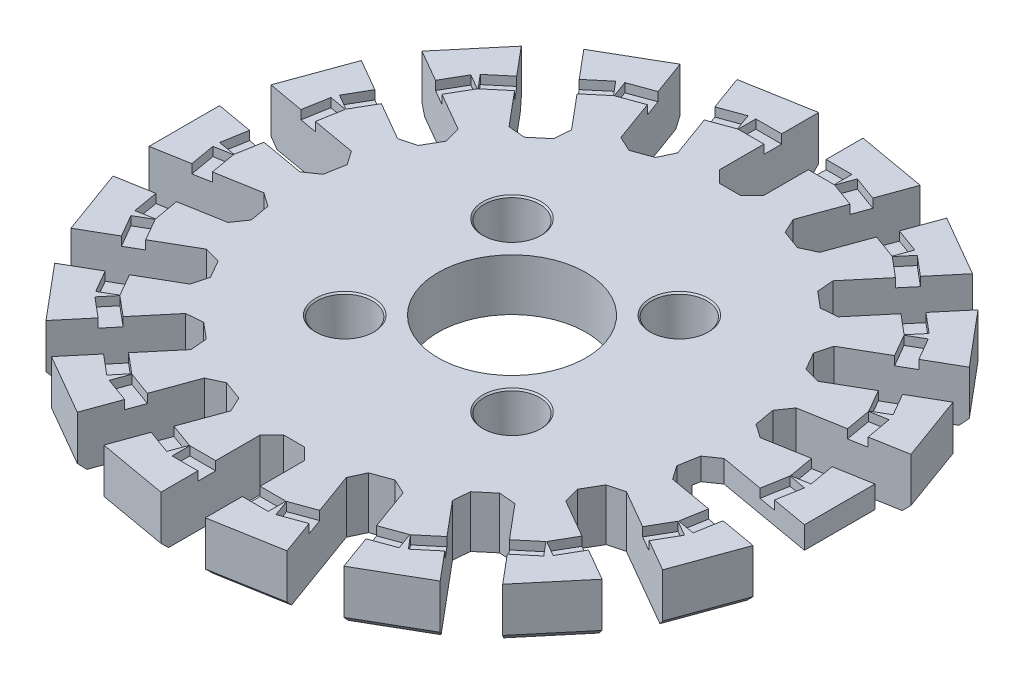
SolidWorks part; units mm, degrees
ref_plane "Front Plane" through (0, 0, 0) normal (0, 0, 1) x (1, 0, 0)
ref_plane "Top Plane" through (0, 0, 0) normal (0, 1, 0) x (1, 0, 0)
ref_plane "Right Plane" through (0, 0, 0) normal (1, 0, 0) x (0, 0, -1)
sketch "Sketch1" plane through (0, 0, 0) normal (0, 1, 0) x (1, 0, 0)
  line L0 (-1.5, 22.2355) -> (-1.5, 14.7355)
  line L1 (-1.5, 22.2355) -> (-6.1955, 21.4076)
  line L2 (-9.0145, 20.3815) -> (-13.1436, 17.9976)
  line L3 (-15.4418, 16.0692) -> (-18.5065, 12.4168)
  line L4 (-20.0065, 9.8187) -> (-21.6372, 5.3384)
  line L5 (-22.1582, 2.3839) -> (-22.1582, -2.3839)
  line L6 (-21.6372, -5.3384) -> (-20.0065, -9.8187)
  line L7 (-18.5065, -12.4168) -> (-15.4418, -16.0692)
  line L8 (-13.1436, -17.9976) -> (-9.0145, -20.3815)
  line L9 (-6.1955, -21.4076) -> (-1.5, -22.2355)
  line L10 (1.5, -22.2355) -> (6.1955, -21.4076)
  line L11 (9.0145, -20.3815) -> (13.1436, -17.9976)
  line L12 (15.4418, -16.0692) -> (18.5065, -12.4168)
  line L13 (20.0065, -9.8187) -> (21.6372, -5.3384)
  line L14 (22.1582, -2.3839) -> (22.1582, 2.3839)
  line L15 (21.6372, 5.3384) -> (20.0065, 9.8187)
  line L16 (18.5065, 12.4168) -> (15.4418, 16.0692)
  line L17 (13.1436, 17.9976) -> (9.0145, 20.3815)
  line L18 (6.1955, 21.4076) -> (1.5, 22.2355)
  line L19 (-1.5, 14.7355) -> (1.5, 14.7355)
  line L20 (1.5, 14.7355) -> (1.5, 22.2355)
  line L21 (6.4494, 13.3338) -> (9.0145, 20.3815)
  line L22 (3.6303, 14.3599) -> (6.4494, 13.3338)
  line L23 (6.1955, 21.4076) -> (3.6303, 14.3599)
  line L24 (10.6209, 10.3239) -> (15.4418, 16.0692)
  line L25 (8.3227, 12.2522) -> (10.6209, 10.3239)
  line L26 (13.1436, 17.9976) -> (8.3227, 12.2522)
  line L27 (13.5113, 6.0687) -> (20.0065, 9.8187)
  line L28 (12.0113, 8.6668) -> (13.5113, 6.0687)
  line L29 (18.5065, 12.4168) -> (12.0113, 8.6668)
  line L30 (14.7721, 1.0816) -> (22.1582, 2.3839)
  line L31 (14.2512, 4.036) -> (14.7721, 1.0816)
  line L32 (21.6372, 5.3384) -> (14.2512, 4.036)
  line L33 (14.2512, -4.036) -> (21.6372, -5.3384)
  line L34 (14.7721, -1.0816) -> (14.2512, -4.036)
  line L35 (22.1582, -2.3839) -> (14.7721, -1.0816)
  line L36 (12.0113, -8.6668) -> (18.5065, -12.4168)
  line L37 (13.5113, -6.0687) -> (12.0113, -8.6668)
  line L38 (20.0065, -9.8187) -> (13.5113, -6.0687)
  line L39 (8.3227, -12.2522) -> (13.1436, -17.9976)
  line L40 (10.6209, -10.3239) -> (8.3227, -12.2522)
  line L41 (15.4418, -16.0692) -> (10.6209, -10.3239)
  line L42 (3.6303, -14.3599) -> (6.1955, -21.4076)
  line L43 (6.4494, -13.3338) -> (3.6303, -14.3599)
  line L44 (9.0145, -20.3815) -> (6.4494, -13.3338)
  line L45 (-1.5, -14.7355) -> (-1.5, -22.2355)
  line L46 (1.5, -14.7355) -> (-1.5, -14.7355)
  line L47 (1.5, -22.2355) -> (1.5, -14.7355)
  line L48 (-6.4494, -13.3338) -> (-9.0145, -20.3815)
  line L49 (-3.6303, -14.3599) -> (-6.4494, -13.3338)
  line L50 (-6.1955, -21.4076) -> (-3.6303, -14.3599)
  line L51 (-10.6209, -10.3239) -> (-15.4418, -16.0692)
  line L52 (-8.3227, -12.2522) -> (-10.6209, -10.3239)
  line L53 (-13.1436, -17.9976) -> (-8.3227, -12.2522)
  line L54 (-13.5113, -6.0687) -> (-20.0065, -9.8187)
  line L55 (-12.0113, -8.6668) -> (-13.5113, -6.0687)
  line L56 (-18.5065, -12.4168) -> (-12.0113, -8.6668)
  line L57 (-14.7721, -1.0816) -> (-22.1582, -2.3839)
  line L58 (-14.2512, -4.036) -> (-14.7721, -1.0816)
  line L59 (-21.6372, -5.3384) -> (-14.2512, -4.036)
  line L60 (-14.2512, 4.036) -> (-21.6372, 5.3384)
  line L61 (-14.7721, 1.0816) -> (-14.2512, 4.036)
  line L62 (-22.1582, 2.3839) -> (-14.7721, 1.0816)
  line L63 (-12.0113, 8.6668) -> (-18.5065, 12.4168)
  line L64 (-13.5113, 6.0687) -> (-12.0113, 8.6668)
  line L65 (-20.0065, 9.8187) -> (-13.5113, 6.0687)
  line L66 (-8.3227, 12.2522) -> (-13.1436, 17.9976)
  line L67 (-10.6209, 10.3239) -> (-8.3227, 12.2522)
  line L68 (-15.4418, 16.0692) -> (-10.6209, 10.3239)
  line L69 (-3.6303, 14.3599) -> (-6.1955, 21.4076)
  line L70 (-6.4494, 13.3338) -> (-3.6303, 14.3599)
  line L71 (-9.0145, 20.3815) -> (-6.4494, 13.3338)
  arc A0 (6.1516, 21.2871) -> (1.5, 22.1073) centre (0, 0) ccw construction
  arc A1 (13.0613, 17.8994) -> (8.9707, 20.2611) centre (0, 0) ccw construction
  arc A2 (18.3955, 12.3527) -> (15.3594, 15.971) centre (0, 0) ccw construction
  arc A3 (21.511, 5.3161) -> (19.8955, 9.7546) centre (0, 0) ccw construction
  arc A4 (22.032, -2.3617) -> (22.032, 2.3617) centre (0, 0) ccw construction
  arc A5 (19.8955, -9.7546) -> (21.511, -5.3161) centre (0, 0) ccw construction
  arc A6 (-8.9707, 20.2611) -> (-13.0613, 17.8994) centre (0, 0) ccw construction
  arc A7 (-15.3594, 15.971) -> (-18.3955, 12.3527) centre (0, 0) ccw construction
  arc A8 (-19.8955, 9.7546) -> (-21.511, 5.3161) centre (0, 0) ccw construction
  arc A9 (-22.032, 2.3617) -> (-22.032, -2.3617) centre (0, 0) ccw construction
  arc A10 (-21.511, -5.3161) -> (-19.8955, -9.7546) centre (0, 0) ccw construction
  arc A11 (-18.3955, -12.3527) -> (-15.3594, -15.971) centre (0, 0) ccw construction
  arc A12 (-13.0613, -17.8994) -> (-8.9707, -20.2611) centre (0, 0) ccw construction
  arc A13 (-6.1516, -21.2871) -> (-1.5, -22.1073) centre (0, 0) ccw construction
  arc A14 (1.5, -22.1073) -> (6.1516, -21.2871) centre (0, 0) ccw construction
  arc A15 (8.9707, -20.2611) -> (13.0613, -17.8994) centre (0, 0) ccw construction
  arc A16 (15.3594, -15.971) -> (18.3955, -12.3527) centre (0, 0) ccw construction
  arc A17 (-1.5, 22.1073) -> (-6.1516, 21.2871) centre (0, 0) ccw construction
  point P96 (0, 0)
  dimension "D1" = 44.3163
  dimension "D2" = 3
  dimension "D3" = 1.5
  dimension "D4" = 7.5
  dimension "D5" = 18
extrude "Boss-Extrude1" add sketch "Sketch1" along normal blind 3.5
chamfer "Chamfer1" distance 0.8 angle 45 36 edges at (-10.6209, 1.75, 10.3239) (-8.3227, 1.75, 12.2522) (-3.6303, 1.75, 14.3599) (1.5, 1.75, 14.7355) (6.4494, 1.75, 13.3338) (10.6209, 1.75, 10.3239) (13.5113, 1.75, 6.0687) (-6.4494, 1.75, 13.3338) (-1.5, 1.75, 14.7355) (3.6303, 1.75, 14.3599) (8.3227, 1.75, 12.2522) (12.0113, 1.75, 8.6668) (14.7721, 1.75, 1.0816) (14.2512, 1.75, -4.036) (12.0113, 1.75, -8.6668) (8.3227, 1.75, -12.2522) (14.2512, 1.75, 4.036) (14.7721, 1.75, -1.0816) (13.5113, 1.75, -6.0687) (10.6209, 1.75, -10.3239) (3.6303, 1.75, -14.3599) (-1.5, 1.75, -14.7355) (-13.5113, 1.75, -6.0687) (-10.6209, 1.75, -10.3239) (-6.4494, 1.75, -13.3338) (1.5, 1.75, -14.7355) (-3.6303, 1.75, -14.3599) (-8.3227, 1.75, -12.2522) (-12.0113, 1.75, -8.6668) (-14.7721, 1.75, -1.0816) (-14.2512, 1.75, -4.036) (-14.2512, 1.75, 4.036) (-14.7721, 1.75, 1.0816) (-12.0113, 1.75, 8.6668) (-13.5113, 1.75, 6.0687) (6.4494, 1.75, -13.3338)
sketch "Sketch2" plane through (0, 3.5, 0) normal (0, 1, 0) x (1, 0, 0)
  line L0 (-3.25, 19.7355) -> (3.25, 19.7355)
  line L2 (3.25, 19.7355) -> (3.25, 18.5355)
  line L3 (3.25, 18.5355) -> (-3.25, 18.5355)
  line L4 (-3.25, 18.5355) -> (-3.25, 19.7355)
  line L5 (3.2855, 18.5292) -> (3.6959, 19.6569)
  line L6 (3.6959, 19.6569) -> (9.8039, 17.4337)
  line L7 (9.8039, 17.4337) -> (9.3935, 16.3061)
  line L8 (9.3935, 16.3061) -> (3.2855, 18.5292)
  line L9 (9.4248, 16.2881) -> (10.1961, 17.2073)
  line L10 (10.1961, 17.2073) -> (15.1754, 13.0292)
  line L11 (15.1754, 13.0292) -> (14.404, 12.11)
  line L12 (14.404, 12.11) -> (9.4248, 16.2881)
  line L13 (14.4272, 12.0823) -> (15.4665, 12.6823)
  line L14 (15.4665, 12.6823) -> (18.7165, 7.0532)
  line L15 (18.7165, 7.0532) -> (17.6772, 6.4532)
  line L16 (17.6772, 6.4532) -> (14.4272, 12.0823)
  line L17 (17.6896, 6.4193) -> (18.8713, 6.6277)
  line L18 (18.8713, 6.6277) -> (20, 0.2264)
  line L19 (20, 0.2264) -> (18.8183, 0.018)
  line L20 (18.8183, 0.018) -> (17.6896, 6.4193)
  line L21 (18.8183, -0.018) -> (20, -0.2264)
  line L22 (20, -0.2264) -> (18.8713, -6.6277)
  line L23 (18.8713, -6.6277) -> (17.6896, -6.4193)
  line L24 (17.6896, -6.4193) -> (18.8183, -0.018)
  line L25 (17.6772, -6.4532) -> (18.7165, -7.0532)
  line L26 (18.7165, -7.0532) -> (15.4665, -12.6823)
  line L27 (15.4665, -12.6823) -> (14.4272, -12.0823)
  line L28 (14.4272, -12.0823) -> (17.6772, -6.4532)
  line L29 (14.404, -12.11) -> (15.1754, -13.0292)
  line L30 (15.1754, -13.0292) -> (10.1961, -17.2073)
  line L31 (10.1961, -17.2073) -> (9.4248, -16.2881)
  line L32 (9.4248, -16.2881) -> (14.404, -12.11)
  line L33 (9.3935, -16.3061) -> (9.8039, -17.4337)
  line L34 (9.8039, -17.4337) -> (3.6959, -19.6569)
  line L35 (3.6959, -19.6569) -> (3.2855, -18.5292)
  line L36 (3.2855, -18.5292) -> (9.3935, -16.3061)
  line L37 (3.25, -18.5355) -> (3.25, -19.7355)
  line L38 (3.25, -19.7355) -> (-3.25, -19.7355)
  line L39 (-3.25, -19.7355) -> (-3.25, -18.5355)
  line L40 (-3.25, -18.5355) -> (3.25, -18.5355)
  line L41 (-3.2855, -18.5292) -> (-3.6959, -19.6569)
  line L42 (-3.6959, -19.6569) -> (-9.8039, -17.4337)
  line L43 (-9.8039, -17.4337) -> (-9.3935, -16.3061)
  line L44 (-9.3935, -16.3061) -> (-3.2855, -18.5292)
  line L45 (-9.4248, -16.2881) -> (-10.1961, -17.2073)
  line L46 (-10.1961, -17.2073) -> (-15.1754, -13.0292)
  line L47 (-15.1754, -13.0292) -> (-14.404, -12.11)
  line L48 (-14.404, -12.11) -> (-9.4248, -16.2881)
  line L49 (-14.4272, -12.0823) -> (-15.4665, -12.6823)
  line L50 (-15.4665, -12.6823) -> (-18.7165, -7.0532)
  line L51 (-18.7165, -7.0532) -> (-17.6772, -6.4532)
  line L52 (-17.6772, -6.4532) -> (-14.4272, -12.0823)
  line L53 (-17.6896, -6.4193) -> (-18.8713, -6.6277)
  line L54 (-18.8713, -6.6277) -> (-20, -0.2264)
  line L55 (-20, -0.2264) -> (-18.8183, -0.018)
  line L56 (-18.8183, -0.018) -> (-17.6896, -6.4193)
  line L57 (-18.8183, 0.018) -> (-20, 0.2264)
  line L58 (-20, 0.2264) -> (-18.8713, 6.6277)
  line L59 (-18.8713, 6.6277) -> (-17.6896, 6.4193)
  line L60 (-17.6896, 6.4193) -> (-18.8183, 0.018)
  line L61 (-17.6772, 6.4532) -> (-18.7165, 7.0532)
  line L62 (-18.7165, 7.0532) -> (-15.4665, 12.6823)
  line L63 (-15.4665, 12.6823) -> (-14.4272, 12.0823)
  line L64 (-14.4272, 12.0823) -> (-17.6772, 6.4532)
  line L65 (-14.404, 12.11) -> (-15.1754, 13.0292)
  line L66 (-15.1754, 13.0292) -> (-10.1961, 17.2073)
  line L67 (-10.1961, 17.2073) -> (-9.4248, 16.2881)
  line L68 (-9.4248, 16.2881) -> (-14.404, 12.11)
  line L69 (-9.3935, 16.3061) -> (-9.8039, 17.4337)
  line L70 (-9.8039, 17.4337) -> (-3.6959, 19.6569)
  line L71 (-3.6959, 19.6569) -> (-3.2855, 18.5292)
  line L72 (-3.2855, 18.5292) -> (-9.3935, 16.3061)
  line L73 (-22.1582, 2.3839) -> (-22.1582, -2.3839) construction
  point P75 (0, 0)
  dimension "D1" = 6.5
  dimension "D2" = 2.5
  dimension "D3" = 3.25
  dimension "D4" = 1.2
  dimension "D6" = 2.1581
  dimension "D7" = 18.5355
  dimension "D5" = 18
extrude "Cut-Extrude1" cut sketch "Sketch2" against normal blind 0.6
chamfer "Chamfer2" distance 0.5 angle 45 18 edges at (-11.0791, 0, 19.1895) (-16.9741, 0, 14.243) (-20.8219, 0, 7.5785) (-22.1582, 0, 0) (-20.8219, 0, -7.5785) (-16.9741, 0, -14.243) (-11.0791, 0, -19.1895) (-3.8477, 0, -21.8215) (3.8477, 0, -21.8215) (11.0791, 0, -19.1895) (16.9741, 0, -14.243) (20.8219, 0, -7.5785) (22.1582, 0, 0) (20.8219, 0, 7.5785) (16.9741, 0, 14.243) (11.0791, 0, 19.1895) (-3.8477, 0, 21.8215) (3.8477, 0, 21.8215)
sketch "Sketch4" plane through (0, 0, 0) normal (0, -1, 0) x (1, 0, 0)
  line L1 (-5.6569, -5.6569) -> (5.6569, -5.6569) construction
  line L2 (-5.6569, -5.6569) -> (-5.6569, 5.6569) construction
  line L3 (-5.6569, 5.6569) -> (5.6569, 5.6569) construction
  line L4 (5.6569, -5.6569) -> (5.6569, 5.6569) construction
  line L5 (-5.6569, -5.6569) -> (5.6569, 5.6569) construction
  line L6 (-5.6569, 5.6569) -> (5.6569, -5.6569) construction
  circle A8 centre (-5.6569, 5.6569) radius 1.5
  circle A9 centre (5.6569, 5.6569) radius 1.5
  circle A10 centre (5.6569, -5.6569) radius 1.5
  circle A11 centre (-5.6569, -5.6569) radius 1.5
  circle A12 centre (0, 0) radius 5
  point P0 (0, 0)
  dimension "D1" = 16
  dimension "D2" = 3
  dimension "D3" = 10
extrude "Cut-Extrude4" cut sketch "Sketch4" against normal up to surface (3.5 mm away) up to face at (0, 3.5, 0)
sketch "Sketch12" plane through (0, 0, 0) normal (0, -1, 0) x (1, 0, 0)
  line L2 (22.1582, 2.3839) -> (22.1582, -2.3839)
  line L6 (22.1582, 2.3839) -> (4.3951, 2.3839)
  line L7 (4.3951, 2.3839) -> (4.3951, -2.3839)
  line L8 (4.3951, -2.3839) -> (22.1582, -2.3839)
  circle A1 centre (0, 0) radius 5 construction
extrude "Cut-Extrude9" cut sketch "Sketch12" against normal blind 2
sketch "Sketch15" plane through (0, 3.5, 0) normal (0, 1, 0) x (1, 0, 0)
  circle A0 centre (5.6569, 5.6569) radius 1.875
  circle A1 centre (-5.6569, 5.6569) radius 1.875
  circle A2 centre (-5.6569, -5.6569) radius 1.875
  circle A3 centre (5.6569, -5.6569) radius 1.875
  dimension "D1" = 3.75
extrude "Cut-Extrude10" cut sketch "Sketch15" against normal blind 3
chamfer "Chamfer3" distance 0.1 angle 45 4 edges at (5.6569, 3.5, 7.5319) (-5.6569, 3.5, 7.5319) (5.6569, 3.5, -3.7819) (-5.6569, 3.5, -3.7819)
